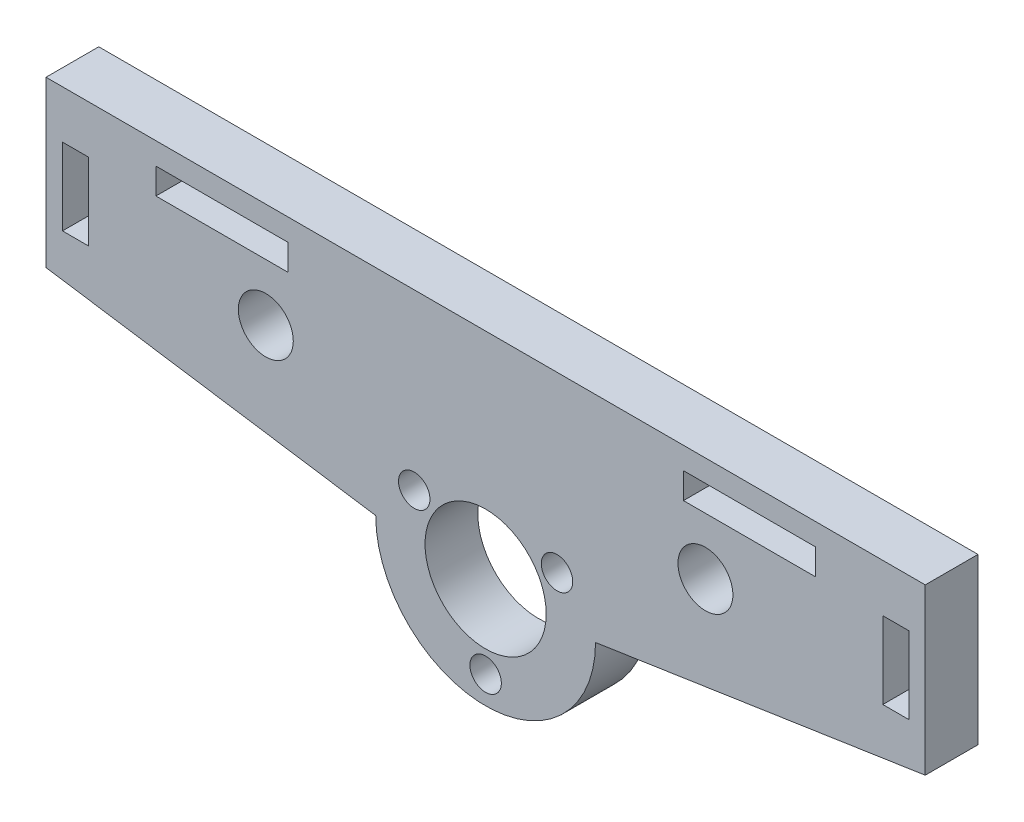
SolidWorks part; units mm, degrees
ref_plane "Front Plane" through (0, 0, 0) normal (0, 0, 1) x (1, 0, 0)
ref_plane "Top Plane" through (0, 0, 0) normal (0, 1, 0) x (1, 0, 0)
ref_plane "Right Plane" through (0, 0, 0) normal (1, 0, 0) x (0, 0, -1)
sketch "Sketch1" plane through (0, 0, 0) normal (0, 0, 1) x (1, 0, 0)
  line L0 (-50.8, 24.815) -> (50.8, 24.815)
  line L1 (-50.8, 24.815) -> (-50.8, 5.765)
  line L2 (-50.8, 5.765) -> (-12.7, 0)
  line L3 (21.0058, 21.005) -> (-21.0058, 21.005) construction
  line L4 (0, 0) -> (0, 24.815) construction
  line L5 (50.8, 24.815) -> (50.8, 5.765)
  line L6 (50.8, 5.765) -> (12.7, 0)
  circle A0 centre (25.4, 12.7) radius 3.175 construction
  circle A1 centre (-25.4, 12.7) radius 3.175 construction
  circle A2 centre (25.4, 12.7) radius 3.175
  circle A3 centre (-25.4, 12.7) radius 3.175
  arc A4 (-12.7, 0) -> (12.7, 0) centre (0, 0) ccw
  circle B0 centre (-8.2489, 4.7625) radius 1.8161
  circle B1 centre (0, 0) radius 7
  circle B2 centre (8.2489, 4.7625) radius 1.8161
  circle B3 centre (0, -9.525) radius 1.8161
  dimension "D3" = 25.4
  dimension "D1" = 19.05
  dimension "D2" = 3.81
  dimension "D4" = 101.6
sketch_block_instance "Threaded Rod Hole attachment-1"
sketch_block "Threaded Rod Hole attachment"
extrude "Boss-Extrude1" add sketch "Sketch1" against normal blind 6.096
sketch "Sketch2" plane through (0, 0, 0) normal (0, 0, 1) x (1, 0, 0)
  line L0 (-50.8, 24.815) -> (-50.8, 5.765) construction
  line L1 (-38.1, 22.275) -> (-22.86, 22.275)
  line L2 (-38.1, 22.275) -> (-38.1, 19.2778)
  line L3 (-38.1, 19.2778) -> (-22.86, 19.2778)
  line L4 (-22.86, 22.275) -> (-22.86, 19.2778)
  line L5 (22.86, 22.275) -> (38.1, 22.275)
  line L6 (22.86, 22.275) -> (22.86, 19.2778)
  line L7 (22.86, 19.2778) -> (38.1, 19.2778)
  line L8 (38.1, 22.275) -> (38.1, 19.2778)
  line L9 (50.8, 5.765) -> (50.8, 24.815) construction
  line L10 (50.8, 24.815) -> (-50.8, 24.815) construction
  dimension "D1" = 12.7
  dimension "D2" = 2.9972
  dimension "D3" = 2.9972
  dimension "D4" = 12.7
  dimension "D5" = 15.24
  dimension "D6" = 2.54
extrude "Cut-Extrude1" cut sketch "Sketch2" against normal through all
sketch "Sketch3" plane through (0, 0, 0) normal (0, 0, 1) x (1, 0, 0)
  line L0 (-38.1, 19.2778) -> (-22.86, 19.2778) construction
  line L1 (-48.895, 19.2778) -> (-45.8978, 19.2778)
  line L2 (-48.895, 19.2778) -> (-48.895, 10.3878)
  line L3 (-48.895, 10.3878) -> (-45.8978, 10.3878)
  line L4 (-45.8978, 19.2778) -> (-45.8978, 10.3878)
  line L5 (-50.8, 24.815) -> (-50.8, 5.765) construction
  line L6 (0, 0) -> (0, 24.815) construction
  line L7 (50.8, 24.815) -> (-50.8, 24.815) construction
  line L8 (45.8978, 19.2778) -> (45.8978, 10.3878)
  line L9 (48.895, 10.3878) -> (45.8978, 10.3878)
  line L10 (48.895, 19.2778) -> (48.895, 10.3878)
  line L11 (48.895, 19.2778) -> (45.8978, 19.2778)
  dimension "D1" = 8.89
  dimension "D2" = 2.9972
  dimension "D3" = 1.905
extrude "Cut-Extrude2" cut sketch "Sketch3" against normal through all
